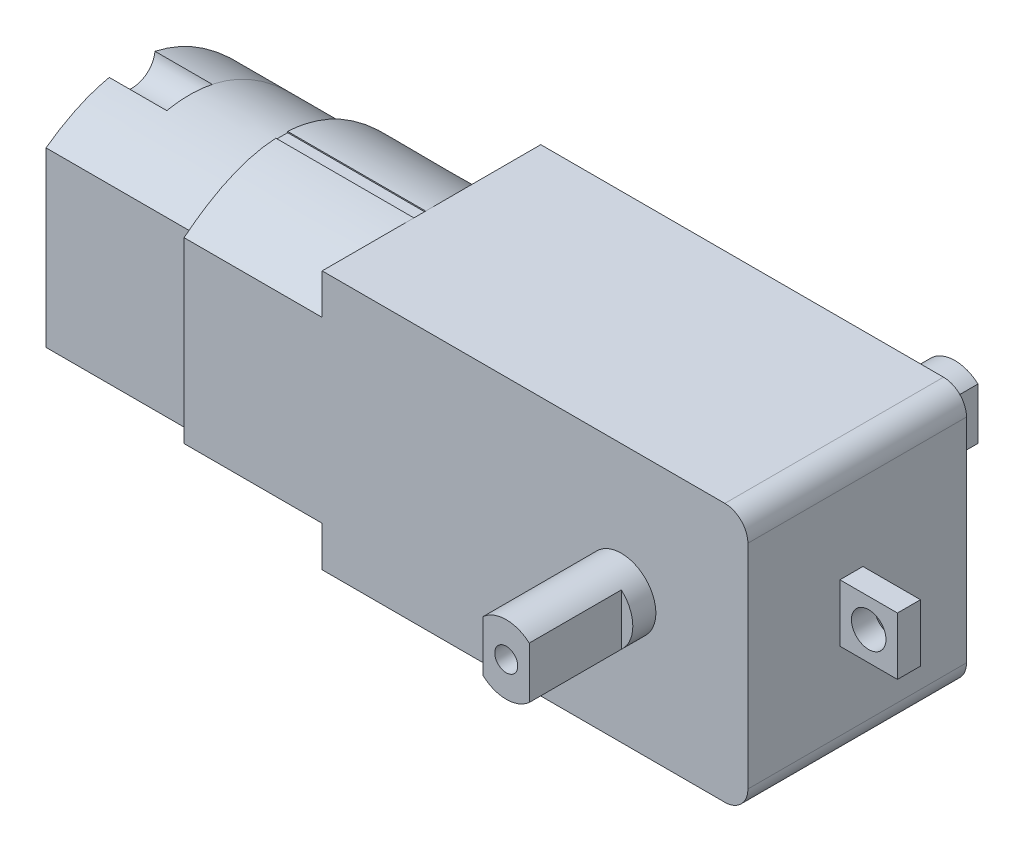
SolidWorks part; units mm, degrees
ref_plane "Plan de face" through (0, 0, 0) normal (0, 0, 1) x (1, 0, 0)
ref_plane "Plan de dessus" through (0, 0, 0) normal (0, 1, 0) x (1, 0, 0)
ref_plane "Plan de droite" through (0, 0, 0) normal (1, 0, 0) x (0, 0, -1)
sketch "Esquisse1" plane through (0, 0, 0) normal (0, 1, 0) x (1, 0, 0)
  line L1 (0, 0) -> (37, 0)
  line L2 (0, 0) -> (0, 19)
  line L3 (0, 19) -> (37, 19)
  line L4 (37, 0) -> (37, 19)
  dimension "D1" = 19
  dimension "D2" = 37
extrude "Boss.-Extru.1" add sketch "Esquisse1" along normal blind 22.5
sketch "Esquisse2" plane through (37, 0, 0) normal (1, 0, 0) x (0, 0, -1)
  line L0 (0, 11.25) -> (19, 11.25) construction
  line L1 (0, 22.5) -> (0, 0) construction
  line L2 (19, 22.5) -> (19, 0) construction
  line L4 (19, 22.5) -> (9, 22.5) construction
  line L5 (0, 22.5) -> (19, 22.5) construction
  line L6 (9, 22.5) -> (9, 0) construction
  line L7 (0, 0) -> (19, 0) construction
  line L8 (8, 11.25) -> (10, 11.25)
  line L9 (10, 11.25) -> (10, 22.5) construction
  line L10 (10, 8.75) -> (10, 13.75)
  line L11 (8, 8.75) -> (8, 13.75)
  line L12 (8, 13.75) -> (10, 13.75)
  line L13 (8, 8.75) -> (10, 8.75)
  point P17 (9, 11.25)
  point P23 (9, 8.75)
  dimension "D1" = 2
  dimension "D2" = 5
  dimension "D3" = 10
  dimension "D4" = 1
  dimension "D5" = 9
extrude "Boss.-Extru.2" add sketch "Esquisse2" along normal blind 5 contours L11 L13 L10 L8 | L12 L11 L8 L10
sketch "Esquisse3" plane through (0, 0, -8) normal (0, 0, 1) x (1, 0, 0)
  line L0 (39.5, 13.75) -> (39.5, 8.75) construction
  line L1 (42, 13.75) -> (37, 13.75) construction
  line L2 (42, 8.75) -> (37, 8.75) construction
  line L3 (42, 11.25) -> (37, 11.25) construction
  line L4 (42, 8.75) -> (42, 13.75) construction
  line L5 (37, 8.75) -> (37, 13.75) construction
  line L6 (39.5, 13.75) -> (39.5, 12.75)
  line L7 (39.5, 8.75) -> (39.5, 9.75)
  line L8 (42, 11.25) -> (41, 11.25)
  line L9 (37, 11.25) -> (38, 11.25)
  line L10 (37, 8.75) -> (42, 13.75) construction
  line L11 (37, 13.75) -> (42, 8.75) construction
  circle A0 centre (39.5, 11.25) radius 1.5
extrude "Enlèv. mat.-Extru.1" cut sketch "Esquisse3" against normal blind 2.4109 contours A0
sketch "Esquisse4" plane through (0, 0, 0) normal (-1, 0, 0) x (0, 0, 1)
  line L0 (-19, 22.5) -> (-18, 22.5)
  line L1 (-19, 22.5) -> (0, 22.5) construction
  line L2 (-18, 22.5) -> (-18, 0) construction
  line L3 (-19, 0) -> (0, 0) construction
  line L4 (-19, 0) -> (-9, 0)
  line L5 (-9, 0) -> (-9, 22.5) construction
  line L6 (-18, 0) -> (-18, 5)
  line L7 (0, 0) -> (0, 3.5)
  line L8 (0, 22.5) -> (0, 0) construction
  line L9 (-19, 11.25) -> (0, 11.25) construction
  line L10 (-19, 22.5) -> (-19, 0) construction
  line L11 (-18, 22.5) -> (-18, 17.5)
  line L12 (0, 22.5) -> (0, 19)
  line L13 (-18, 17.5) -> (-18, 5)
  line L14 (0, 19) -> (0, 3.5)
  line L15 (-18, 5) -> (-18, 6)
  line L16 (-9, 0) -> (-9, 1)
  line L17 (0, 3.5) -> (0, 4.5)
  line L18 (-9, 22.5) -> (-9, 21.5)
  line L19 (0, 19) -> (0, 18)
  line L20 (-18, 17.5) -> (-18, 16.5)
  line L21 (0, 22.5) -> (-1, 22.5)
  line L22 (-1, 22.5) -> (-1, 0)
  line L23 (-18, 22.5) -> (-17, 22.5)
  line L24 (-17, 22.5) -> (-17, 0)
  spline S0 degree 2 poles (-18, 5) (-9.5771, -4.2106) (0, 3.5) knots 0 0 0 1 1 1
  spline S1 degree 2 poles (-18, 17.5) (-9.5771, 26.7106) (0, 19) knots 0 0 0 1 1 1
  spline S2 degree 2 poles (-18, 6) (-9.5771, -3.2106) (0, 4.5) knots 0 0 0 1 1 1
  spline S3 degree 2 poles (-18, 16.5) (-9.5771, 25.7106) (0, 18) knots 0 0 0 1 1 1
  line M10 (-19, 0) -> (0, 0)
  line M11 (0, 0) -> (0, 22.5)
  line M12 (0, 22.5) -> (-19, 22.5)
extrude "Boss.-Extru.3" add sketch "Esquisse4" along normal blind 12 contours L24 S3 L18 S1 | L18 S3 L22 S1 M12 | L22 S3 S1 M11 | S3 L22 S2 L14 | S2 L16 S0 L22 M10 | S2 L22 S0 M11 | S2 L24 S0 L16 | S2 L13 S0 L24 | S3 L13 S2 L24 | L13 S3 L24 S1
sketch "Esquisse9" plane through (-12, 0, 0) normal (-1, 0, 0) x (0, 0, 1)
  line L0 (-8.4875, 22.5) -> (-8.4875, 0) construction
  line L1 (-7.9751, 22.5) -> (-9, 22.5) construction
  line L2 (-9, 0) -> (-7.9751, 0) construction
  line M1 (-1, 18.7612) -> (-1, 3.7388)
  spline M2 degree 2 poles (0, 4.5) (-9.5771, -3.2106) (-18, 6) knots 0 0 0 1 1 1 only from (-1, 3.7388) to (-17, 4.97)
  line M3 (-17, 4.97) -> (-17, 17.53)
  spline M4 degree 2 poles (-18, 16.5) (-9.5771, 25.7106) (0, 18) knots 0 0 0 1 1 1 only from (-17, 17.53) to (-1, 18.7612)
extrude "Boss.-Extru.4" add sketch "Esquisse9" along normal blind 8 separate body contours L0 M4 M2 M1 | L0 M4 M3 M2
sketch "Esquisse10" plane through (-20, 0, 0) normal (-1, 0, 0) x (0, 0, 1)
  line L0 (-8.4875, 22.5) -> (-8.4875, 0) construction
  line L1 (-7.9751, 22.5) -> (-9, 22.5) construction
  line L2 (-9, 0) -> (-7.9751, 0) construction
  line L3 (-19, 11.25) -> (0, 11.25) construction
  line L4 (-19, 22.5) -> (-19, 0) construction
  line L5 (0, 3.5) -> (0, 19) construction
  line L6 (-17, 4.97) -> (-17, 17.53) construction
  line L7 (-17, 11.25) -> (-16.9, 11.25)
  line L8 (-1, 11.25) -> (-1.1, 11.25)
  line L9 (-1, 18.7612) -> (-1, 3.7388) construction
  line L15 (-6.4955, 21.3113) -> (-6.4955, 21.3266)
  line L16 (-17, -3.3338) -> (-17, 29.7131) construction
  line L17 (-1, -3.3338) -> (-1, 24.1363) construction
  line L19 (-17, -3.3338) -> (-1, -3.3338)
  line L20 (-17, -3.3338) -> (-17, 23.254)
  line L21 (-17, 23.254) -> (-1, 23.254)
  line L22 (-1, -3.3338) -> (-1, 23.254)
  arc A0 (-6.4955, 1.1887) -> (-10.4791, 1.194) centre (-8.4875, 0.9864) ccw
  arc A1 (-6.564, 22.0613) -> (-10.3404, 22.2666) centre (-8.4875, 21.5136) cw
  parabola Q0 (-1, 3.7388) -> (-17, 4.97) focus (-8.8172, 5.8055) apex (-9.1443, 1.0088) construction
  parabola Q1 (-1, 3.7388) -> (-17, 4.97) focus (-8.8172, 5.8055) apex (-9.1443, 1.0088) construction
  parabola Q7 (-17, 17.53) -> (-1, 18.7612) focus (-8.8172, 16.6945) apex (-9.1443, 21.4912) construction
  parabola Q27 (-1, 3.7388) -> (-17, 4.97) focus (-8.8172, 5.8055) apex (-9.1443, 1.0088) construction
  parabola Q44 (-17, 17.53) -> (-1, 18.7612) focus (-8.8172, 16.6945) apex (-9.1443, 21.4912) construction
  spline S0 degree 2 poles (-17, 4.97) (-9.2856, -2.3255) (-1, 3.7388) knots 0 0 0 1 1 1
  spline S1 degree 2 poles (-17, 17.53) (-9.2856, 24.8255) (-1, 18.7612) knots 0 0 0 1 1 1
  spline S2 degree 1 poles (-1, 18.7612) (-1, 3.7388) knots 0 0 1 1
  point P14 (-17, 11.25)
  point P16 (-17, 11.25)
  point P37 (-42.7272, 14.6576)
  point P42 (-8.4875, 21.5136)
  point P54 (-8.4875, 21.5136)
  point P60 (-8.4875, 0.9864)
  point P61 (-8.4875, 0.9864)
extrude "Boss.-Extru.5" add sketch "Esquisse10" along normal blind 5
sketch "Esquisse11" plane through (-25, 0, 0) normal (-1, 0, 0) x (0, 0, 1)
  line L0 (-8.4764, 19.5136) -> (-8.4764, 2.9887) construction
  line L1 (-1, 11.25) -> (-17, 11.25) construction
  line L2 (-1, 3.7388) -> (-1, 18.7612) construction
  line L3 (-17, 17.53) -> (-17, 4.97) construction
  line L4 (-17, 11.25) -> (-12, 11.25)
  line L5 (-12, 11.25) -> (-12, 23.9143) construction
  line L6 (-12, 23.9143) -> (-12, -3.0888) construction
  line L7 (-12, 14.8173) -> (-12, 7.6331)
  line L8 (-1, 18.7612) -> (-1, 3.7388) construction
  arc A0 (-10.475, 21.2896) -> (-6.4978, 21.3117) centre (-8.4875, 21.5136) ccw construction
  arc A1 (-6.4955, 1.1887) -> (-10.4772, 1.2109) centre (-8.4875, 0.9864) ccw construction
  circle A3 centre (-8.4764, 11.2511) radius 5
extrude "Boss.-Extru.6" add sketch "Esquisse11" along normal blind 2 contours L7 A3
sketch "Esquisse13" plane through (-27, 0, 0) normal (-1, 0, 0) x (0, 0, 1)
  line L0 (-8.4875, 0) -> (-8.4875, 22.5)
  line L1 (-9, 0) -> (-7.9751, 0) construction
  line L2 (-7.9751, 22.5) -> (-9, 22.5) construction
  line L3 (-19, 11.25) -> (0, 11.25) construction
  line L4 (-19, 22.5) -> (-19, 0) construction
  line L5 (0, 3.5) -> (0, 19) construction
  circle A0 centre (-8.4875, 11.25) radius 2
  circle A1 centre (-8.4875, 11.25) radius 1
extrude "Boss.-Extru.8" add sketch "Esquisse13" along normal blind 1 contours L0 L3 A1 | L3 L0 A1 | L3 A1 L0 | A1 L3 L0
sketch "Esquisse14" plane through (-27, 0, 0) normal (-1, 0, 0) x (0, 0, 1)
  line L0 (-19, 11.25) -> (0, 11.25)
  line L1 (-19, 22.5) -> (-19, 0) construction
  line L2 (0, 3.5) -> (0, 19) construction
  line L3 (-8.4875, 22.5) -> (-8.4875, 0) construction
  line L4 (-7.9751, 22.5) -> (-9, 22.5) construction
  line L5 (-9, 0) -> (-7.9751, 0) construction
  circle A0 centre (-8.4875, 11.25) radius 2
  circle M3 centre (-8.4875, 11.25) radius 1
extrude "Enlèv. mat.-Extru.2" cut sketch "Esquisse14" against normal blind 1 contours A0 L3 L0 M3 | L3 A0 L0 M3 | L3 L0 A0 M3 | L3 A0 L0 M3
sketch "Esquisse15" plane through (0, 0, -19) normal (0, 0, -1) x (-1, 0, 0)
  line L0 (-18.5, 22.5) -> (-18.5, 0) construction
  line L1 (-37, 22.5) -> (0, 22.5) construction
  line L2 (-37, 0) -> (0, 0) construction
  line L3 (-37, 11.25) -> (0, 11.25) construction
  line L4 (-37, 8.75) -> (-37, 13.75) construction
  line L5 (0, 17.5) -> (0, 5) construction
  line L6 (-37, 11.25) -> (-26, 11.25)
  line L7 (-26, 11.25) -> (-24.9, 11.25)
  line L8 (-26, 11.25) -> (-26, 22.5) construction
  line L9 (-26, 22.5) -> (-26, 0) construction
  line L10 (-26, 0) -> (-24.9, 0) construction
  line L11 (-24.9, 0) -> (-24.9, 22.5) construction
  line L12 (-24.9, 14.7323) -> (-24.9, 8.25)
  line L13 (-27.1, 0) -> (-27.1, 22.5) construction
  line L14 (-27.1, 8.25) -> (-27.1, 14.7323)
  circle A0 centre (-26, 11.25) radius 3
  dimension "D1" = 11
extrude "Boss.-Extru.11" add sketch "Esquisse15" along normal blind 10 contours L14 A0 L12 L7 L6 | L12 A0 L14 L6 L7 | L12 A0 | L14 A0 L6 | L6 A0 L14
sketch "Esquisse19" plane through (0, 0, -29) normal (0, 0, -1) x (-1, 0, 0)
  line L0 (-37, 11.25) -> (0, 11.25) construction
  line L1 (-37, 8.75) -> (-37, 13.75) construction
  line L2 (0, 22.5) -> (0, 0) construction
  line L3 (-37, 22.5) -> (-26, 22.5) construction
  line L4 (-37, 22.5) -> (0, 22.5) construction
  line L5 (-26, 22.5) -> (-26, 0) construction
  line L6 (-37, 0) -> (0, 0) construction
  line L7 (-28, 22.5) -> (-24, 22.5)
  line L8 (-24, 22.5) -> (-24, 0) construction
  line L9 (-28, 22.5) -> (-28, 0) construction
  line L10 (-24, 14.6381) -> (-24, 6.3768)
  line L11 (-28, 14.6381) -> (-28, 6.3768)
  circle A1 centre (-26, 11.25) radius 3
  circle M2 centre (-26, 11.25) radius 3
  dimension "D1" = 2
extrude "Enlèv. mat.-Extru.3" cut sketch "Esquisse19" against normal blind 8 contours L10 M2 | L11 M2
sketch "Esquisse20" plane through (0, 0, -29) normal (0, 0, -1) x (-1, 0, 0)
  line L0 (-37, 11.25) -> (0, 11.25) construction
  line L1 (-37, 8.75) -> (-37, 13.75) construction
  line L2 (0, 22.5) -> (0, 0) construction
  line L3 (-26, 11.25) -> (-26, 22.5) construction
  line L4 (-37, 22.5) -> (0, 22.5) construction
  line L5 (-26, 22.5) -> (-26, 0) construction
  line L6 (-37, 0) -> (0, 0) construction
  circle A0 centre (-26, 11.25) radius 1
extrude "Enlèv. mat.-Extru.4" cut sketch "Esquisse20" against normal blind 12
sketch3d "Esquisse3D1"
  line L6 (37, 0, -9.5) -> (37, 29.4998, -9.5) construction
  line L7 (37, 0, 0) -> (37, 0, -19) construction
sketch3d "Esquisse3D2" plane through (0, 0, 0) normal (0, 0, 1) x (1, 0, 0)
sketch "Esquisse21" plane through (0, 0, 0) normal (0, 0, 1) x (1, 0, 0)
  line L0 (-12, 11.25) -> (37, 11.25) construction
  line L1 (-12, 3.5) -> (-12, 19) construction
  line L2 (37, 0) -> (37, 29.4998) construction
  line L3 (37, 22.5) -> (26, 22.5)
  line L4 (0, 22.5) -> (37, 22.5) construction
  line L5 (26, 22.5) -> (26, 0) construction
  line L6 (0, 0) -> (37, 0) construction
  circle A0 centre (26, 11.25) radius 3
  dimension "D1" = 11
extrude "Boss.-Extru.12" add sketch "Esquisse21" along normal blind 10 contours A0
sketch "Esquisse22" plane through (0, 0, 10) normal (0, 0, 1) x (1, 0, 0)
  line L0 (-12, 11.25) -> (37, 11.25) construction
  line L1 (-12, 3.5) -> (-12, 19) construction
  line L2 (37, 0) -> (37, 29.4998) construction
  line L3 (37, 22.5) -> (26, 22.5)
  line L4 (0, 22.5) -> (37, 22.5) construction
  line L5 (26, 22.5) -> (26, 0) construction
  line L6 (0, 0) -> (37, 0) construction
  circle A0 centre (26, 11.25) radius 1
extrude "Enlèv. mat.-Extru.5" cut sketch "Esquisse22" against normal blind 12 contours A0
sketch "Esquisse23" plane through (0, 0, 10) normal (0, 0, 1) x (1, 0, 0)
  line L0 (37, 22.5) -> (26, 22.5)
  line L1 (0, 22.5) -> (37, 22.5) construction
  line L2 (-12, 11.25) -> (37, 11.25) construction
  line L3 (-12, 18.7612) -> (-12, 3.7388) construction
  line L4 (37, 0) -> (37, 29.4998) construction
  line L5 (26, 22.5) -> (27.7275, 22.5)
  line L6 (24, 11.25) -> (28, 11.25)
  line L7 (28, 11.25) -> (28, 22.5) construction
  line L8 (28, 22.5) -> (28, 0) construction
  line L9 (0, 0) -> (37, 0) construction
  line L10 (26, 22.5) -> (26, 0) construction
  line L11 (24, 11.25) -> (24, 22.5) construction
  line L12 (24, 22.5) -> (24, 0) construction
  line L13 (28, 8.5115) -> (28, 14.0659)
  line L14 (24, 7.9416) -> (24, 14.0659)
  point P21 (26, 11.25)
  circle M5 centre (26, 11.25) radius 3
extrude "Enlèv. mat.-Extru.6" cut sketch "Esquisse23" against normal blind 8 contours L13 M5 | L14 M5
fillet "Congé1" radius 2 1 edges at (37, 22.5, -9.5)
fillet "Congé2" radius 2 1 edges at (37, 0, -9.5)
sketch "Esquisse24" plane through (-25, 0, 0) normal (-1, 0, 0) x (0, 0, 1)
sketch "Esquisse25" plane through (0, 0, 0) normal (0, -1, 0) x (1, 0, 0)
  line L0 (-12, -7.9751) -> (0, -7.9751)
  line L1 (0, 0) -> (0, -19)
  line L2 (-12, -7.9751) -> (-12, -9)
  line L3 (-12, -9) -> (0, -9)
  line L4 (0, -7.9751) -> (0, -9)
extrude "Enlèv. mat.-Extru.8" cut sketch "Esquisse25" against normal blind 0.1
sketch "Esquisse26" plane through (0, 22.5, 0) normal (0, 1, 0) x (1, 0, 0)
  line L0 (0, 9) -> (0, 7.9751)
  line L1 (0, 7.9751) -> (-12, 7.9751)
  line L2 (-12, 7.9751) -> (-12, 9)
  line L3 (-12, 9) -> (0, 9)
extrude "Enlèv. mat.-Extru.9" cut sketch "Esquisse26" against normal blind 0.1 contours L3 L0 L1 L2
